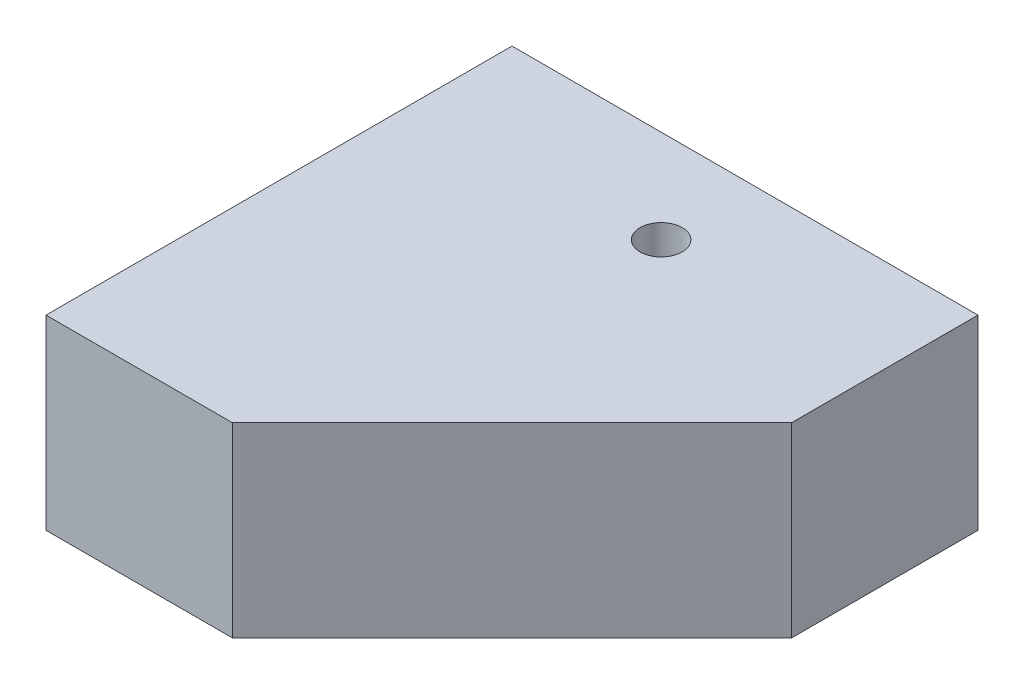
SolidWorks part; units mm, degrees
ref_plane "Front Plane" through (0, 0, 0) normal (0, 0, 1) x (1, 0, 0)
ref_plane "Top Plane" through (0, 0, 0) normal (0, 1, 0) x (1, 0, 0)
ref_plane "Right Plane" through (0, 0, 0) normal (1, 0, 0) x (0, 0, -1)
sketch "Sketch1" plane through (0, 0, 0) normal (0, 1, 0) x (1, 0, 0)
  line L0 (0, 0) -> (0, 25)
  line L1 (0, 25) -> (25, 25)
  line L2 (25, 25) -> (25, 15)
  line L3 (25, 15) -> (10, 0)
  line L4 (10, 0) -> (0, 0)
  dimension "D1" = 25
  dimension "D3" = 10
extrude "Boss-Extrude1" add sketch "Sketch1" along normal blind 10
hole_wizard "#4-40 Tapped Hole1" positions "Sketch2" profile "Sketch3" tap size "#4-40" standard "ANSI Inch"
sketch "Sketch2" plane through (0, 0, 0) normal (-1, 0, 0) x (0, 0, 1)
  line L0 (-25, 5) -> (0, 5) construction
  line L1 (-25, 10) -> (-25, 0) construction
  line L2 (0, 10) -> (0, 0) construction
  point P0 (-15, 5)
  dimension "D1" = 10
sketch "Sketch3" plane through (0, 5, -15) normal (0, 1, 0) x (0, 0, 1)
  line L0 (0, 0) -> (0, 10.6792)
  line L1 (0, 10.6792) -> (1.1303, 10)
  line L2 (1.1303, 10) -> (1.1303, 0)
  line L5 (1.1303, 0) -> (0, 0)
  line L10 (0, 10.6792) -> (-1.1303, 10) construction
  line L11 (0, -6.35) -> (0, 107.95) construction
  dimension "Tap Drill Dia." = 2.2606
  dimension "Tap Drill Depth" = 10
  dimension "Drill Angle" = 118
hole_wizard "#4-40 Tapped Hole2" positions "Sketch4" profile "Sketch5" tap size "#4-40" standard "ANSI Inch"
sketch "Sketch4" plane through (0, 10, 0) normal (0, 1, 0) x (1, 0, 0)
  line L0 (25, 25) -> (0, 25) construction
  line L1 (0, 25) -> (0, 0) construction
  point P0 (13, 20)
  dimension "D1" = 5
  dimension "D2" = 13
sketch "Sketch5" plane through (13, 10, -20) normal (1, 0, 0) x (0, 0, 1)
  line L0 (0, 0) -> (0, 10.6792)
  line L1 (0, 10.6792) -> (1.1303, 10)
  line L2 (1.1303, 10) -> (1.1303, 0)
  line L5 (1.1303, 0) -> (0, 0)
  line L10 (0, 10.6792) -> (-1.1303, 10) construction
  line L11 (0, -6.35) -> (0, 107.95) construction
  dimension "Tap Drill Dia." = 2.2606
  dimension "Tap Drill Depth" = 10
  dimension "Drill Angle" = 118
hole_wizard "#4-40 Tapped Hole3" positions "Sketch6" profile "Sketch7" tap size "#4-40" standard "ANSI Inch"
sketch "Sketch6" plane through (0, 0, -25) normal (0, 0, -1) x (-1, 0, 0)
  line L0 (0, 5) -> (-25, 5) construction
  line L1 (0, 10) -> (0, 0) construction
  line L2 (-25, 10) -> (-25, 0) construction
  point P0 (-18, 5)
  dimension "D1" = 18
sketch "Sketch7" plane through (18, 5, -25) normal (1, 0, 0) x (0, 1, 0)
  line L0 (0, 0) -> (0, 10.6792)
  line L1 (0, 10.6792) -> (1.1303, 10)
  line L2 (1.1303, 10) -> (1.1303, 0)
  line L5 (1.1303, 0) -> (0, 0)
  line L10 (0, 10.6792) -> (-1.1303, 10) construction
  line L11 (0, -6.35) -> (0, 107.95) construction
  dimension "Tap Drill Dia." = 2.2606
  dimension "Tap Drill Depth" = 10
  dimension "Drill Angle" = 118
